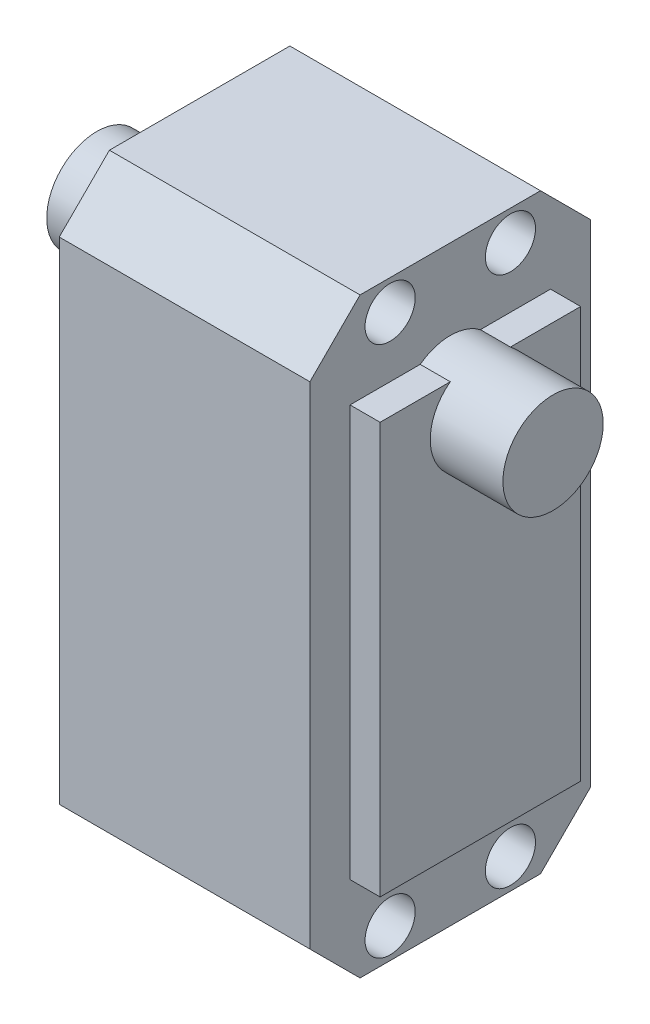
SolidWorks part; units mm, degrees
ref_plane "Front Plane" through (0, 0, 0) normal (0, 0, 1) x (1, 0, 0)
ref_plane "Top Plane" through (0, 0, 0) normal (0, 1, 0) x (1, 0, 0)
ref_plane "Right Plane" through (0, 0, 0) normal (1, 0, 0) x (0, 0, -1)
sketch "Sketch1" plane through (0, 0, 0) normal (0, 0, 1) x (1, 0, 0)
  line L1 (0, 0) -> (2.5, 0)
  line L2 (0, 0) -> (0, 6.3)
  line L3 (0, 6.3) -> (2.5, 6.3)
  line L4 (2.5, 0) -> (2.5, 6.3)
  dimension "D1" = 6.3
  dimension "D2" = 2.5
extrude "Boss-Extrude2" add sketch "Sketch1" along normal blind 2.8
sketch "Sketch3" plane through (2.5, 0, 0) normal (1, 0, 0) x (0, 0, -1)
  line L0 (-1.4, 6.3) -> (-1.4, 0) construction
  line L1 (-2.8, 6.3) -> (0, 6.3) construction
  line L2 (-2.8, 0) -> (0, 0) construction
  line L3 (-2.4, 5.2) -> (-2.4, 1.1)
  line L4 (-0.4, 5.2) -> (-0.4, 1.1)
  line L5 (-2.4, 0) -> (-0.4, 0) construction
  line L6 (-2.4, 6.3) -> (-0.4, 6.3) construction
  line L8 (-2.4, 5.2) -> (-0.4, 5.2)
  line L9 (-2.4, 1.1) -> (-0.4, 1.1)
  line L11 (-2.4, 6.3) -> (-2.4, 0) construction
  line L12 (-0.4, 6.3) -> (-0.4, 0) construction
  dimension "D1" = 1
  dimension "D2" = 1
  dimension "D3" = 1.1
  dimension "D4" = 1.1
extrude "Boss-Extrude3" add sketch "Sketch3" along normal blind 0.3
ref_plane "Plane1" through (1.25, 0, 0) normal (1, 0, 0) x (0, 0, -1)
sketch "Sketch4" plane through (0, 0, 0) normal (-1, 0, 0) x (0, 0, 1)
  line L0 (1.4, 6.3) -> (1.4, 0) construction
  line L1 (2.8, 6.3) -> (0, 6.3) construction
  line L2 (2.8, 0) -> (0, 0) construction
  line L3 (0.4, 5.2) -> (0.4, 1.1)
  line L4 (2.4, 5.2) -> (2.4, 1.1)
  line L5 (0.4, 0) -> (2.4, 0) construction
  line L6 (0.4, 6.3) -> (2.4, 6.3) construction
  line L8 (0.4, 5.2) -> (2.4, 5.2)
  line L9 (0.4, 1.1) -> (2.4, 1.1)
  line L11 (0.4, 6.3) -> (0.4, 0) construction
  line L12 (2.4, 6.3) -> (2.4, 0) construction
  dimension "D1" = 1
  dimension "D2" = 1
  dimension "D3" = 1.1
  dimension "D4" = 1.1
extrude "Boss-Extrude4" add sketch "Sketch4" along normal blind 0.3
sketch "Sketch5" plane through (0, 0, 0) normal (-1, 0, 0) x (0, 0, 1)
  line L0 (1.4, 0) -> (1.4, 1.1) construction
  line L1 (2.8, 0) -> (0, 0) construction
  line L2 (0.4, 1.1) -> (2.4, 1.1) construction
  line L3 (1.4, 1.1) -> (1.4, 5.2) construction
  line L4 (2.4, 5.2) -> (0.4, 5.2) construction
  line L5 (1.4, 5.2) -> (1.4, 6.3) construction
  line L6 (2.8, 6.3) -> (0, 6.3) construction
  line L13 (0.8, 1.1) -> (2, 1.1) construction
  line L14 (0.8, 5.2) -> (2, 5.2) construction
  line L21 (1.75, 0.5) -> (2, 0.5)
  circle A0 centre (0.8, 0.5) radius 0.25
  circle A1 centre (2, 0.5) radius 0.25
  circle A2 centre (0.8, 5.8) radius 0.25
  circle A3 centre (2, 5.8) radius 0.25
  dimension "D5" = 0.5
  dimension "D6" = 0.5
  dimension "D7" = 0.5
  dimension "D8" = 0.5
extrude "Cut-Extrude1" cut sketch "Sketch5" against normal blind 10.3
sketch "Sketch6" plane through (1.25, 0, 0) normal (1, 0, 0) x (0, 0, -1)
  line L0 (-1.4, 6.3) -> (-1.4, 4.8) construction
  line L1 (-2.8, 6.3) -> (0, 6.3) construction
  circle A0 centre (-1.4, 4.8) radius 0.5
  dimension "D2" = 1
  dimension "D1" = 1.5
fillet "Fillet1" radius 0.2 4 edges at (1.25, 0, 2.8) (1.25, 0, 0) (1.25, 6.3, 0) (1.25, 6.3, 2.8)
extrude "Boss-Extrude5" add sketch "Sketch6" along normal mid plane 4.55
sketch "Sketch7" plane through (0, 0, 0) normal (-1, 0, 0) x (0, 0, 1)
  line L0 (0, 6.1) -> (2.8, 6.1)
  line L1 (2.8, 6.1) -> (2.8, 6.3)
  line L2 (2.8, 6.3) -> (2.6, 6.3)
  line L3 (2.6, 6.3) -> (0.2, 6.3)
  line L4 (0.2, 6.3) -> (0, 6.3)
  line L5 (0, 6.3) -> (0, 6.1)
  line L6 (0, 0.2) -> (2.8, 0.2)
  line L7 (2.8, 0.2) -> (2.8, 0)
  line L8 (2.8, 0) -> (2.6, 0)
  line L9 (2.6, 0) -> (0.2, 0)
  line L10 (2.6, 0) -> (0.2, 0) construction
  line L11 (0.2, 0) -> (0, 0)
  line L12 (0, 0) -> (0, 0.2)
  arc A0 (0, 0.2) -> (0.2, 0) centre (0.2, 0.2) ccw construction
extrude "Cut-Extrude2" cut sketch "Sketch7" against normal blind 10
sketch "Sketch8" plane through (0, 0, 0) normal (-1, 0, 0) x (0, 0, 1)
  line L0 (2.8, 6.1) -> (2.8, 5.6)
  line L1 (2.8, 6.1) -> (2.8, 0.2) construction
  line L2 (2.8, 6.1) -> (2.3, 6.1)
  line L3 (0, 6.1) -> (2.8, 6.1) construction
  line L4 (2.3, 6.1) -> (2.8, 5.6)
  line L5 (0, 6.1) -> (0.5, 6.1)
  line L6 (0.5, 6.1) -> (0, 5.6)
  line L7 (0, 6.1) -> (0, 0.2) construction
  line L8 (0, 5.6) -> (0, 6.1)
  line L9 (0, 0.2) -> (0, 0.7)
  line L10 (0, 0.7) -> (0.5, 0.2)
  line L11 (2.8, 0.2) -> (0, 0.2) construction
  line L12 (0.5, 0.2) -> (0, 0.2)
  line L13 (2.8, 0.2) -> (2.8, 0.7)
  line L14 (2.8, 0.7) -> (2.3, 0.2)
  line L15 (2.3, 0.2) -> (2.8, 0.2)
  dimension "D1" = 0.5
  dimension "D2" = 0.5
  dimension "D3" = 0.5
  dimension "D4" = 0.5
  dimension "D5" = 0.5
  dimension "D6" = 0.5
  dimension "D7" = 0.5
  dimension "D8" = 0.5
extrude "Cut-Extrude3" cut sketch "Sketch8" against normal blind 10
